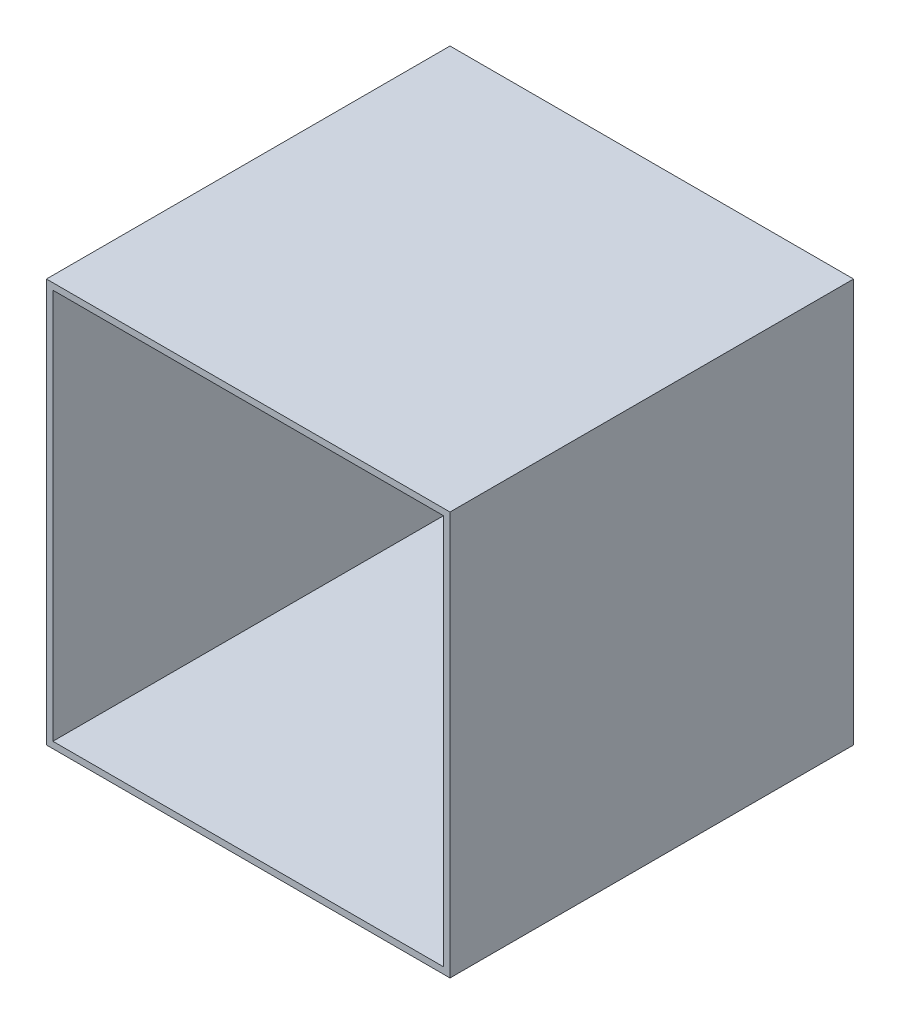
SolidWorks part; units mm, degrees
ref_plane "Front Plane" through (0, 0, 0) normal (0, 0, 1) x (1, 0, 0)
ref_plane "Top Plane" through (0, 0, 0) normal (0, 1, 0) x (1, 0, 0)
ref_plane "Right Plane" through (0, 0, 0) normal (1, 0, 0) x (0, 0, -1)
sketch "Sketch1" plane through (0, 0, 0) normal (0, 0, 1) x (1, 0, 0)
  line L1 (-12.1, 12.1) -> (12.1, 12.1)
  line L2 (-12.1, 12.1) -> (-12.1, -12.1)
  line L3 (-12.1, -12.1) -> (12.1, -12.1)
  line L4 (12.1, 12.1) -> (12.1, -12.1)
  line L5 (-12.1, 12.1) -> (12.1, -12.1) construction
  line L6 (-12.1, -12.1) -> (12.1, 12.1) construction
  line L7 (-12.5, 12.5) -> (12.5, 12.5)
  line L8 (-12.5, 12.5) -> (-12.5, -12.5)
  line L9 (-12.5, -12.5) -> (12.5, -12.5)
  line L10 (12.5, 12.5) -> (12.5, -12.5)
  line L11 (-12.5, 12.5) -> (12.5, -12.5) construction
  line L12 (-12.5, -12.5) -> (12.5, 12.5) construction
  point P0 (0, 0)
  point P7 (0, 0)
  dimension "D1" = 0.4
  dimension "D2" = 0.4
  dimension "D3" = 25
extrude "Boss-Extrude1" add sketch "Sketch1" along normal blind 25
fillet "Fillet1" [suppressed] radius 2
fillet "Fillet2" [suppressed] radius 2.4
